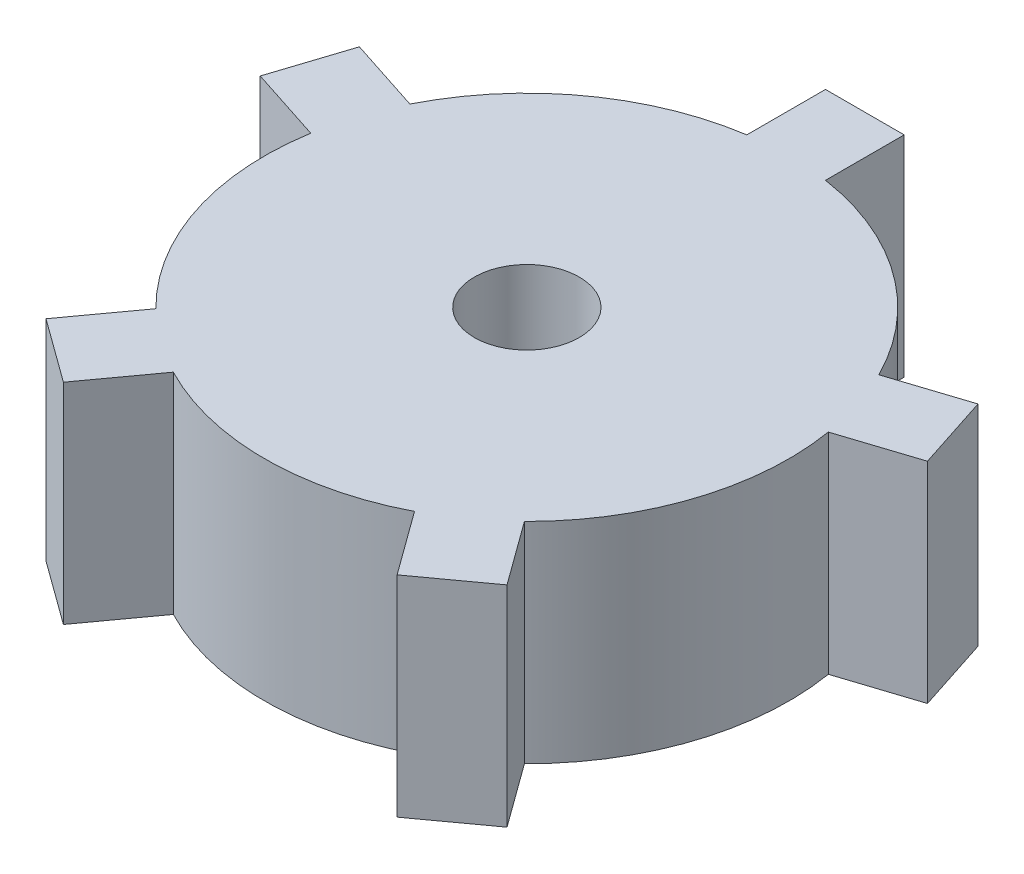
SolidWorks part; units mm, degrees
ref_plane "Front Plane" through (0, 0, 0) normal (0, 0, 1) x (1, 0, 0)
ref_plane "Top Plane" through (0, 0, 0) normal (0, 1, 0) x (1, 0, 0)
ref_plane "Right Plane" through (0, 0, 0) normal (1, 0, 0) x (0, 0, -1)
sketch "Sketch1" plane through (0, 0, 0) normal (0, 1, 0) x (1, 0, 0)
  line L0 (29.4815, 13.5221) -> (31.7991, 6.3892)
  line L2 (-3.75, 24.7171) -> (-3.75, 32.2171)
  line L3 (-3.75, 32.2171) -> (3.75, 32.2171)
  line L4 (3.75, 24.7171) -> (3.75, 32.2171)
  line L5 (0, 28) -> (3.75, 32.2171) construction
  line L6 (-3.75, 32.2171) -> (0, 28) construction
  line L7 (22.3486, 11.2045) -> (29.4815, 13.5221)
  line L8 (24.6662, 4.0716) -> (31.7991, 6.3892)
  line L9 (21.9706, -23.86) -> (15.903, -28.2684)
  line L10 (17.5622, -17.7924) -> (21.9706, -23.86)
  line L11 (11.4946, -22.2008) -> (15.903, -28.2684)
  line L12 (-15.903, -28.2684) -> (-21.9706, -23.86)
  line L13 (-11.4946, -22.2008) -> (-15.903, -28.2684)
  line L14 (-17.5622, -17.7924) -> (-21.9706, -23.86)
  line L15 (-31.7991, 6.3892) -> (-29.4815, 13.5221)
  line L16 (-24.6662, 4.0716) -> (-31.7991, 6.3892)
  line L17 (-22.3486, 11.2045) -> (-29.4815, 13.5221)
  arc A0 (-3.75, 24.7171) -> (-22.3486, 11.2045) centre (0, 0) ccw
  arc A1 (-24.6662, 4.0716) -> (-17.5622, -17.7924) centre (0, 0) ccw
  arc A2 (-11.4946, -22.2008) -> (11.4946, -22.2008) centre (0, 0) ccw
  arc A3 (17.5622, -17.7924) -> (24.6662, 4.0716) centre (0, 0) ccw
  arc A4 (22.3486, 11.2045) -> (3.75, 24.7171) centre (0, 0) ccw
  circle A5 centre (0, 0) radius 5
  point P3 (0, 28)
  point P26 (0, 0)
  dimension "D1" = 50
  dimension "D6" = 10
  dimension "D2" = 28
  dimension "D4" = 7.5
  dimension "D5" = 7.5
  dimension "D3" = 5
extrude "Boss-Extrude1" add sketch "Sketch1" along normal blind 20
